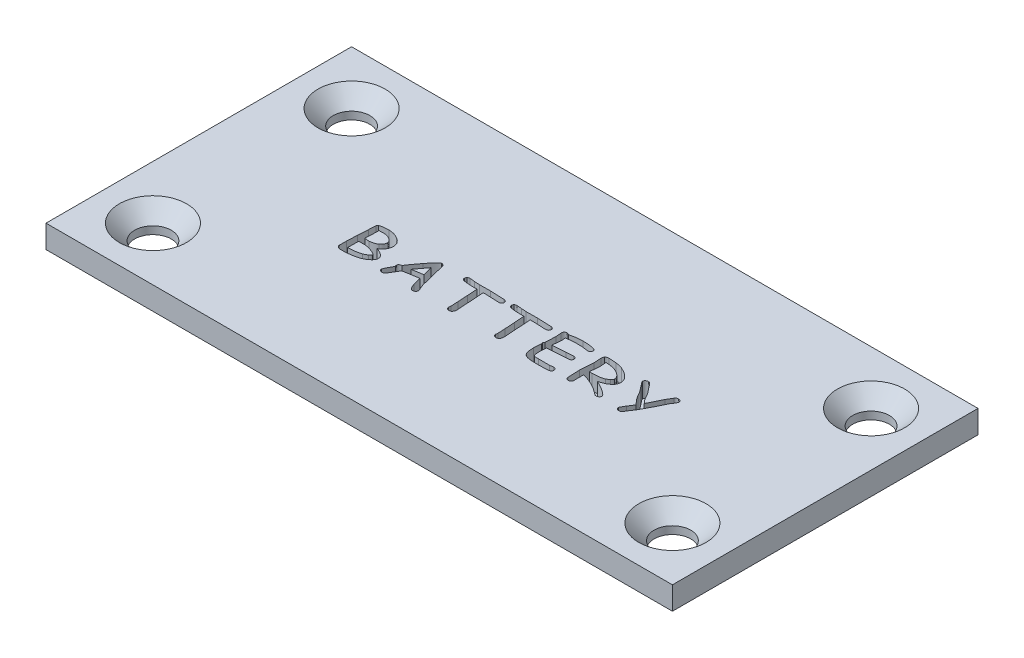
SolidWorks part; units mm, degrees
ref_plane "Front Plane" through (0, 0, 0) normal (0, 0, 1) x (1, 0, 0)
ref_plane "Top Plane" through (0, 0, 0) normal (0, 1, 0) x (1, 0, 0)
ref_plane "Right Plane" through (0, 0, 0) normal (1, 0, 0) x (0, 0, -1)
sketch "Sketch1" plane through (0, 0, 0) normal (0, 1, 0) x (1, 0, 0)
  line L9 (0, 0) -> (41, 0)
  line L10 (0, 0) -> (0, 20)
  line L11 (0, 20) -> (41, 20)
  line L12 (41, 0) -> (41, 20)
  dimension "D1" = 41
  dimension "D2" = 20
extrude "Boss-Extrude2" add sketch "Sketch1" along normal blind 1.5
hole_wizard "CSK for M2 Flat Head Machine Screw1" positions "3DSketch1" profile "Sketch2" countersink size "M2" standard "ANSI Metric"
sketch3d "3DSketch1"
  line L0 (0, 1.5, -20) -> (0, 1.5, 0) construction
  line L1 (0, 1.5, 0) -> (41, 1.5, 0) construction
  line L2 (41, 1.5, -20) -> (0, 1.5, -20) construction
  line L3 (41, 1.5, 0) -> (41, 1.5, -20) construction
  point P0 (3.5, 1.5, -3.5)
  point P2 (3.5, 1.5, -16.5)
  point P4 (37.5, 1.5, -16.5)
  point P6 (37.5, 1.5, -3.5)
  dimension "D1" = 3.5
  dimension "D2" = 3.5
  dimension "D3" = 3.5
  dimension "D4" = 3.5
  dimension "D5" = 3.5
  dimension "D6" = 3.5
  dimension "D7" = 3.5
  dimension "D8" = 3.5
sketch "Sketch2" plane through (3.5, 1.5, -3.5) normal (1, 0, 0) x (0, 0, 1)
  line L0 (0, 0) -> (0, 3.871)
  line L1 (0, 3.871) -> (1.2, 3.15)
  line L2 (1.2, 3.15) -> (1.2, 1)
  line L3 (1.2, 1) -> (2.2, 0)
  line L5 (2.2, 0) -> (0, 0)
  line L6 (-1.2, 1) -> (-2.2, 0) construction
  line L10 (0, 3.871) -> (-1.2, 3.15) construction
  line L11 (0, -6.35) -> (0, 107.95) construction
  dimension "Hole Dia." = 2.4
  dimension "Hole Depth" = 3.15
  dimension "Near C'Sink Dia." = 4.4
  dimension "Near C'Sink Angle" = 90
  dimension "Drill Angle" = 118
sketch "Sketch3" plane through (0, 1.5, 0) normal (0, 1, 0) x (1, 0, 0)
  line L0 (10.4737, 8.2369) -> (30.5263, 8.2369) construction
  line L1 (0, 0) -> (41, 0) construction
  text T0 "BATTERY" font "Comic Sans MS" height 2.5
  point P2 (20.5, 8.2369)
  point P5 (20.5, 0)
extrude "BatteryText" cut sketch "Sketch3" against normal blind 1
